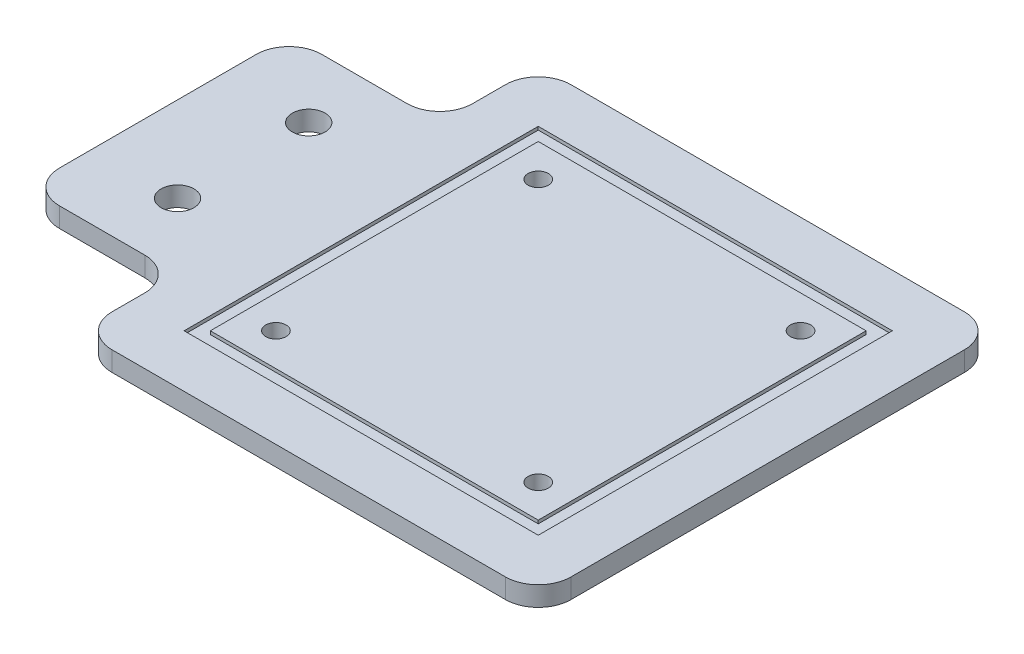
SolidWorks part; units mm, degrees
ref_plane "Front Plane" through (0, 0, 0) normal (0, 0, 1) x (1, 0, 0)
ref_plane "Top Plane" through (0, 0, 0) normal (0, 1, 0) x (1, 0, 0)
ref_plane "Right Plane" through (0, 0, 0) normal (1, 0, 0) x (0, 0, -1)
sketch "Sketch1" plane through (0, 0, 0) normal (0, 0, 1) x (1, 0, 0)
  line L0 (0, 0) -> (0, 23)
  line L1 (0, 23) -> (23, 23)
  line L2 (23, 23) -> (23, 20)
  line L3 (23, 20) -> (3, 20)
  line L4 (3, 20) -> (3, 0)
  line L5 (3, 0) -> (0, 0)
  dimension "D1" = 20
  dimension "D2" = 3
  dimension "D3" = 3
extrude "Boss-Extrude1" add sketch "Sketch1" along normal blind 40
sketch "Sketch2" plane through (0, 23, 0) normal (0, 1, 0) x (1, 0, 0)
  line L0 (23, 0) -> (0, 0) construction
  circle A0 centre (13, -10) radius 2.5
  circle A1 centre (13, -30) radius 2.5
  dimension "D3" = 5
  dimension "D1" = 20
  dimension "D2" = 10
  dimension "D4" = 10
extrude "Cut-Extrude1" cut sketch "Sketch2" against normal up to next
sketch "Sketch3" plane through (0, 0, 0) normal (-1, 0, 0) x (0, 0, 1)
  line L1 (40, 23) -> (40, 0) construction
  line L2 (40, 0) -> (0, 0) construction
  circle A0 centre (10, 10) radius 2.5
  circle A1 centre (30, 10) radius 2.5
  dimension "D1" = 5
  dimension "D2" = 20
  dimension "D3" = 10
  dimension "D4" = 10
extrude "Cut-Extrude2" cut sketch "Sketch3" against normal up to next
sketch "Sketch4" plane through (0, 23, 0) normal (0, 1, 0) x (1, 0, 0)
  line L0 (-1000, -20) -> (49000, -20) construction
  line L1 (0, -40) -> (0, 0) construction
  line L2 (23, -40) -> (23, 0) construction
  line L3 (93, -55) -> (23, -55)
  line L4 (93, -55) -> (93, 15)
  line L5 (93, 15) -> (23, 15)
  line L6 (23, -55) -> (23, 15)
  line L7 (93, -55) -> (23, 15) construction
  line L8 (93, 15) -> (23, -55) construction
  point P1 (58, -20)
  point P5 (0, -20)
  dimension "D1" = 70
  dimension "D2" = 70
extrude "Boss-Extrude2" add sketch "Sketch4" against normal up to surface (3 mm away) up to face at (10.5, 20, 10)
sketch "Sketch8" plane through (0, 23, 0) normal (0, 1, 0) x (1, 0, 0)
  line L0 (-1000, -20) -> (49000, -20) construction
  line L1 (33, -45) -> (83, -45)
  line L2 (33, -45) -> (33, 5)
  line L3 (33, 5) -> (83, 5)
  line L4 (83, -45) -> (83, 5)
  line L5 (33, -45) -> (83, 5) construction
  line L6 (33, 5) -> (83, -45) construction
  line L7 (0, -40) -> (0, 0) construction
  line L8 (58, -980) -> (58, 49020) construction
  line L9 (93, 15) -> (23, 15) construction
  line L10 (31, 7) -> (85, 7)
  line L11 (85, -47) -> (85, 7)
  line L12 (31, -47) -> (85, -47)
  line L13 (31, -47) -> (31, 7)
  point P0 (58, -20)
  point P10 (0, -20)
  point P11 (0, 0)
  point P15 (58, 15)
  dimension "D1" = 50
  dimension "D2" = 50
  dimension "D3" = 2
extrude "Cut-Extrude7" cut sketch "Sketch8" against normal blind 0.5
sketch "Sketch9" plane through (0, 23, 0) normal (0, 1, 0) x (1, 0, 0)
  line L0 (33, 5) -> (33, -45) construction
  line L1 (83, 5) -> (33, 5) construction
  circle A0 centre (38, -40) radius 1.55
  circle A1 centre (38, 0) radius 1.55
  circle A2 centre (78, 0) radius 1.55
  circle A3 centre (78, -40) radius 1.55
  point P8 (62.6296, -5.8784)
  point P9 (0, 0)
  dimension "D2" = 40
  dimension "D4" = 5
  dimension "D5" = 3.1
  dimension "D1" = 5
  dimension "D3" = 40
extrude "Cut-Extrude8" cut sketch "Sketch9" against normal up to next
sketch "Sketch10" plane through (0, 0, 0) normal (-1, 0, 0) x (0, 0, 1)
  line L1 (0, 0) -> (40, 0)
  line L2 (0, 0) -> (0, 20)
  line L3 (0, 20) -> (40, 20)
  line L4 (40, 0) -> (40, 20)
extrude "Cut-Extrude9" cut sketch "Sketch10" against normal up to next
fillet "Fillet1" radius 5 8 edges at (93, 21.5, 55) (93, 21.5, -15) (23, 21.5, -15) (23, 21.5, 0) (23, 21.5, 40) (23, 21.5, 55) (0, 21.5, 40) (0, 21.5, 0)
